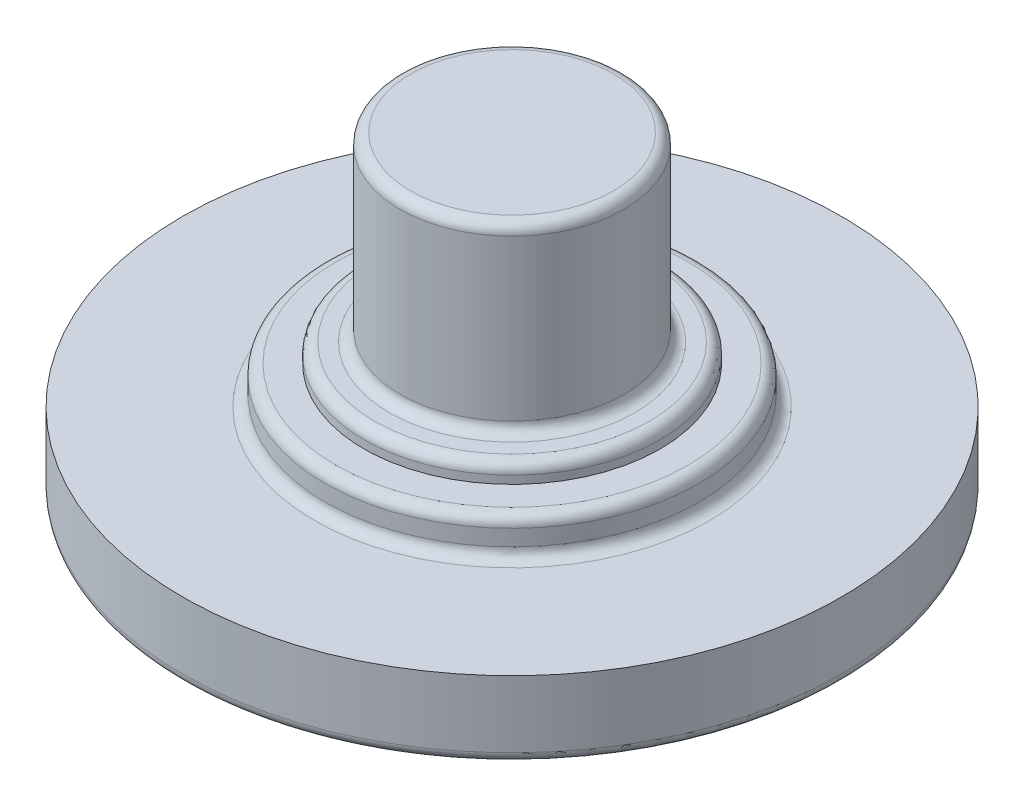
SolidWorks part; units mm, degrees
ref_plane "Plano frontal" through (0, 0, 0) normal (0, 0, 1) x (1, 0, 0)
ref_plane "Plano superior" through (0, 0, 0) normal (0, 1, 0) x (1, 0, 0)
ref_plane "Plano direito" through (0, 0, 0) normal (1, 0, 0) x (0, 0, -1)
sketch "Esboço1" plane through (0, 0, 0) normal (0, 0, 1) x (1, 0, 0)
  line L0 (0, 52.9543) -> (0, -74.2559) construction
  line L1 (0, 52.9543) -> (21, 52.9543)
  line L2 (21, 52.9543) -> (21, 18.9543)
  line L3 (21, 18.9543) -> (27.75, 18.9543)
  line L4 (27.75, 18.9543) -> (27.75, 15.4543)
  line L5 (27.75, 15.4543) -> (35, 15.4543)
  line L6 (35, 15.4543) -> (35, 8.4543)
  line L7 (35, 8.4543) -> (61.75, 8.4543)
  line L8 (61.75, 8.4543) -> (61.75, -6.0457)
  line L9 (61.75, -6.0457) -> (34, -6.0457)
  line L10 (34, -6.0457) -> (34, -11.7457)
  line L11 (34, -11.7457) -> (30, -11.7457)
  line L12 (30, -11.7457) -> (30, -26.5457)
  line L13 (30, -26.5457) -> (23, -26.5457)
  line L14 (23, -26.5457) -> (23, -22.5457)
  line L15 (23, -22.5457) -> (19.6341, -9.0457)
  line L16 (19.6341, -9.0457) -> (0, -9.0457)
  line L17 (0, -9.0457) -> (0, 52.9543)
  dimension "D1" = 21
  dimension "D2" = 27.75
  dimension "D3" = 35
  dimension "D4" = 61.75
  dimension "D5" = 14
  dimension "D6" = 23
  dimension "D7" = 17.5
  dimension "D8" = 4
  dimension "D9" = 5.7
  dimension "D10" = 20.5
  dimension "D11" = 14.5
  dimension "D12" = 7
  dimension "D13" = 3.5
  dimension "D14" = 79.5
  dimension "D15" = 30
  dimension "D16" = 34
revolve "Revolução1" add sketch "Esboço1" angle 360 about L0
fillet "Filete4" radius 2 1 edges at (-21, 52.9543, 0)
fillet "Filete5" radius 2 2 edges at (-27.75, 18.9543, 0) (-21, 18.9543, 0)
fillet "Filete6" radius 2 3 edges at (-61.75, -6.0457, 0) (-35, 8.4543, 0) (-35, 15.4543, 0)
fillet "Filete7" radius 2 1 edges at (-34, -6.0457, 0)
fillet "Filete9" radius 3 3 edges at (-19.6341, -9.0457, 0) (-23, -26.5457, 0) (-30, -11.7457, 0)
fillet "Filete10" radius 0.5 1 edges at (-30, -26.5457, 0)
